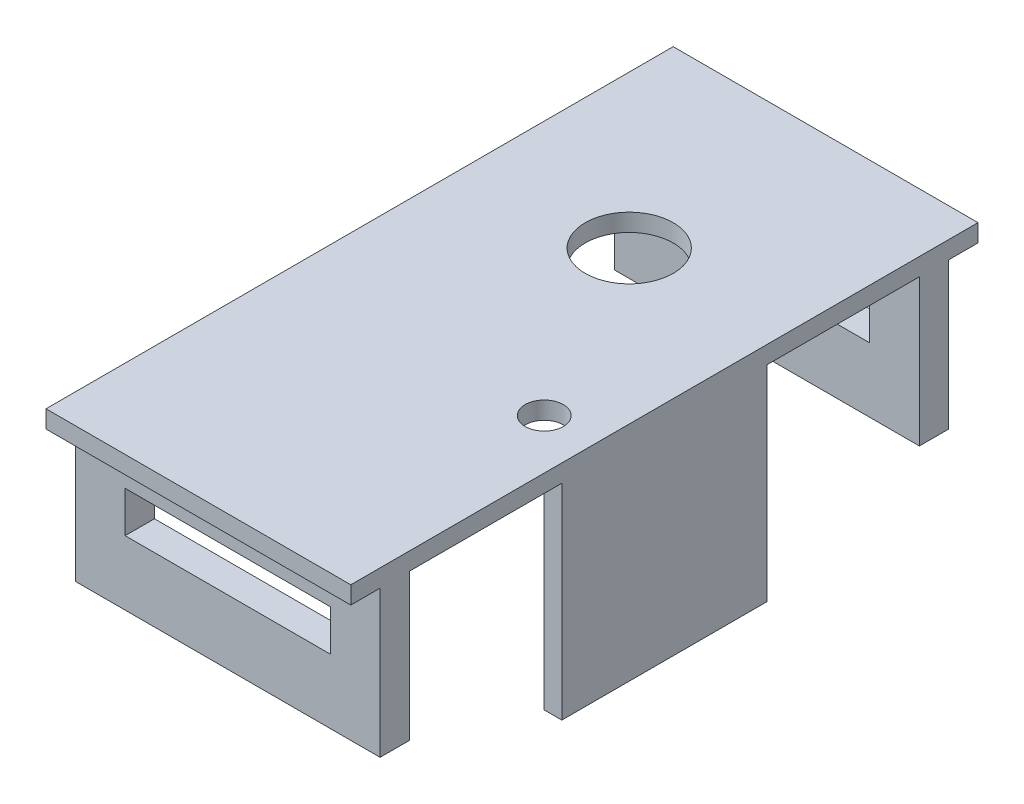
SolidWorks part; units mm, degrees
ref_plane "Front" through (0, 0, 0) normal (0, 0, 1) x (1, 0, 0)
ref_plane "Top" through (0, 0, 0) normal (0, 1, 0) x (1, 0, 0)
ref_plane "Right" through (0, 0, 0) normal (1, 0, 0) x (0, 0, -1)
sketch "Sketch1" plane through (0, 0, 0) normal (0, 1, 0) x (1, 0, 0)
  line L1 (26, -53.5) -> (-26, -53.5)
  line L2 (26, -53.5) -> (26, 53.5)
  line L3 (26, 53.5) -> (-26, 53.5)
  line L4 (-26, -53.5) -> (-26, 53.5)
  line L5 (26, -53.5) -> (-26, 53.5) construction
  line L6 (26, 53.5) -> (-26, -53.5) construction
  line L11 (12.5, 45.7212) -> (-12.5, 25.7212) construction
  line L12 (12.5, 25.7212) -> (-12.5, 45.7212) construction
  line L17 (-11.5, 14) -> (11.5, -38) construction
  line L18 (-11.5, -38) -> (11.5, 14) construction
  circle A0 centre (17.5, -12) radius 3.25
  point P0 (0, 0)
  point P6 (0, 35.7212)
  point P12 (0, -12)
  dimension "D8" = 6.5
  dimension "D1" = 52
  dimension "D6" = 107
  dimension "D7" = 12
extrude "Boss-Extrude1" add sketch "Sketch1" along normal blind 3
sketch "Sketch2" plane through (0, 0, 0) normal (0, -1, 0) x (1, 0, 0)
  line L0 (-26, -53.5) -> (-26, 53.5) construction
  line L1 (-26, 17.5) -> (-23, 17.5)
  line L2 (-26, 17.5) -> (-26, -17.5)
  line L3 (-26, -17.5) -> (-23, -17.5)
  line L4 (-23, 17.5) -> (-23, -17.5)
  line L5 (26, 53.5) -> (26, -53.5) construction
  line L6 (26, 17.5) -> (23, 17.5)
  line L7 (26, 17.5) -> (26, -17.5)
  line L8 (26, -17.5) -> (23, -17.5)
  line L9 (23, 17.5) -> (23, -17.5)
  point P12 (23, 0)
  point P14 (-23, 0)
  dimension "D1" = 3
  dimension "D2" = 3
  dimension "D3" = 35
extrude "Boss-Extrude2" add sketch "Sketch2" along normal blind 35
sketch "Sketch3" plane through (0, 0, 0) normal (0, -1, 0) x (1, 0, 0)
  line L0 (-26, 17.5) -> (-26, 53.5) construction
  line L1 (-26, 48.5) -> (26, 48.5)
  line L2 (-26, 48.5) -> (-26, 43.5)
  line L3 (-26, 43.5) -> (26, 43.5)
  line L4 (26, 48.5) -> (26, 43.5)
  line L5 (26, 53.5) -> (26, 17.5) construction
  line L6 (26, -17.5) -> (26, -53.5) construction
  line L7 (26, -43.5) -> (-26, -43.5)
  line L8 (26, -43.5) -> (26, -48.5)
  line L9 (26, -48.5) -> (-26, -48.5)
  line L10 (-26, -43.5) -> (-26, -48.5)
  line L11 (-26, 53.5) -> (26, 53.5) construction
  line L12 (26, -53.5) -> (-26, -53.5) construction
  line L13 (-26, -53.5) -> (-26, -17.5) construction
  dimension "D1" = 5
  dimension "D2" = 5
  dimension "D3" = 5
extrude "Boss-Extrude3" add sketch "Sketch3" along normal blind 25
sketch "Sketch4" plane through (0, 3, 0) normal (0, 1, 0) x (1, 0, 0)
  circle A0 centre (0, 20) radius 7.5
  point P2 (0, 0)
  dimension "D1" = 15
  dimension "D2" = 20
extrude "Cut-Extrude1" cut sketch "Sketch4" against normal through all
sketch "Sketch5" plane through (0, 0, -48.5) normal (0, 0, -1) x (-1, 0, 0)
  line L1 (-17.5, -7) -> (17.5, -7)
  line L2 (-17.5, -7) -> (-17.5, -14)
  line L3 (-17.5, -14) -> (17.5, -14)
  line L4 (17.5, -7) -> (17.5, -14)
  point P4 (0, -7)
  dimension "D1" = 7
  dimension "D2" = 35
  dimension "D3" = 7
extrude "Cut-Extrude2" cut sketch "Sketch5" against normal through all both and the other way through all
